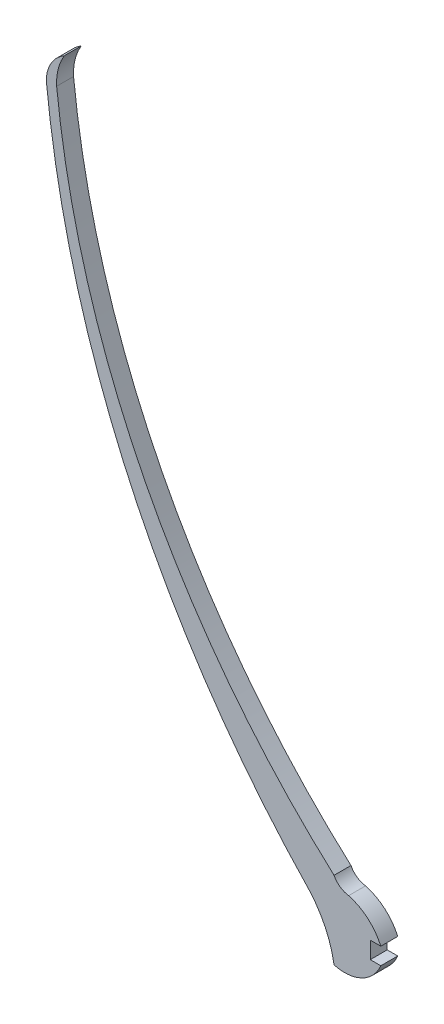
SolidWorks part; units mm, degrees
ref_plane "Front Plane" through (0, 0, 0) normal (0, 0, 1) x (1, 0, 0)
ref_plane "Top Plane" through (0, 0, 0) normal (0, 1, 0) x (1, 0, 0)
ref_plane "Right Plane" through (0, 0, 0) normal (1, 0, 0) x (0, 0, -1)
sketch "Sketch1" plane through (0, 0, 0) normal (0, 0, 1) x (1, 0, 0)
  line L0 (-12.3905, 0) -> (-12.3905, -1.524)
  line L1 (-12.3905, -1.524) -> (-11.4405, -1.524)
  line L2 (-12.3905, 0) -> (-11.4405, 0)
  arc A0 (-11.4405, -1.524) -> (-15.6522, -3.5607) centre (-14.6976, -0.1617) cw
  arc A1 (-15.6522, -3.5607) -> (-17.8982, 1.1579) centre (-24.8054, -5.0237) ccw
  arc A2 (-17.8982, 1.1579) -> (-41.5713, 52.4722) centre (45.0263, 61.305) cw
  arc A3 (-11.4405, 0) -> (-14.338, 2.4964) centre (-15.5298, -1.8165) ccw
  arc A4 (-14.338, 2.4964) -> (-15.6522, 3.425) centre (-14.113, 4.2091) cw
  arc A5 (-15.6522, 3.425) -> (-40.6365, 52.4722) centre (35.9656, 60.6058) cw
  arc A6 (-41.5713, 52.4722) -> (-39.9529, 55.1926) centre (-38.3565, 52.4013) cw
  arc A7 (-39.9529, 55.1926) -> (-40.6365, 52.4722) centre (-35.8947, 52.7267) ccw
extrude "Boss-Extrude1" add sketch "Sketch1" along normal blind 1.524
